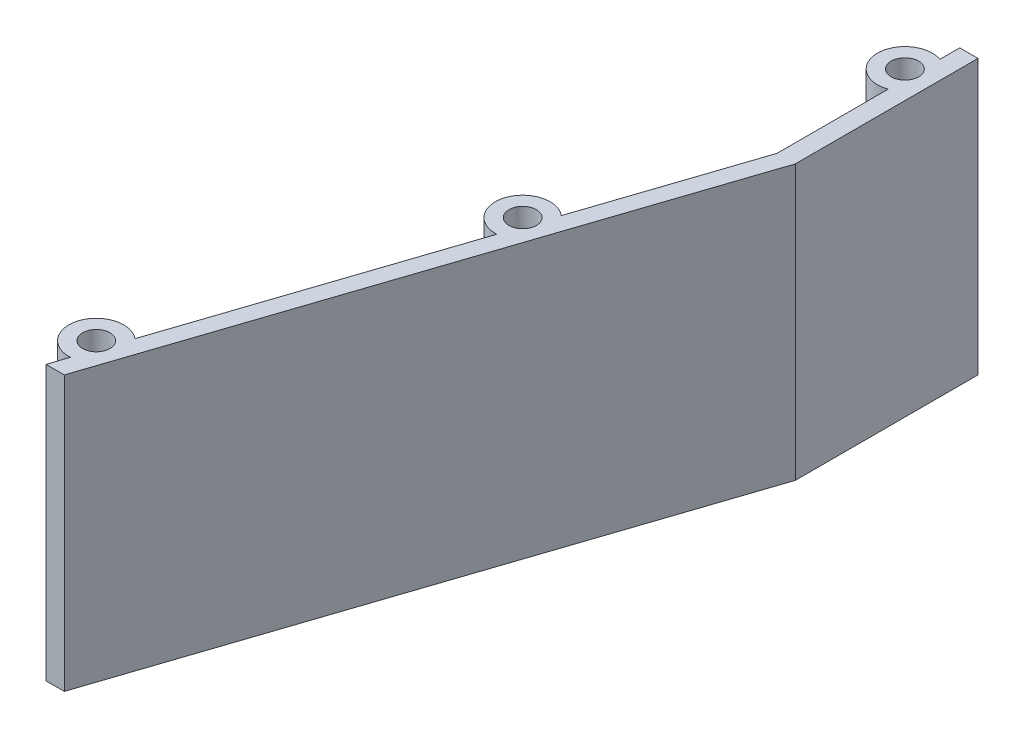
SolidWorks part; units mm, degrees
ref_plane "前视基准面" through (0, 0, 0) normal (0, 0, 1) x (1, 0, 0)
ref_plane "上视基准面" through (0, 0, 0) normal (0, 1, 0) x (1, 0, 0)
ref_plane "右视基准面" through (0, 0, 0) normal (1, 0, 0) x (0, 0, -1)
other "Configuration Table"
sketch "草图1" plane through (0, 0, 0) normal (0, 1, 0) x (1, 0, 0)
  line L0 (0, 0) -> (-5.9006, -17.7018)
  line L1 (-20, -60) -> (-18, -60)
  line L2 (-18, -60) -> (2, 0)
  line L3 (2, 0) -> (2, 20)
  line L4 (2, 20) -> (0, 20)
  line L5 (0, 20) -> (0, 17.8284)
  line L6 (-13.6514, -60) -> (49986.3486, -60) construction
  line L7 (2, 0) -> (0, 0) construction
  line L8 (0, 0) -> (0, -50000) construction
  line L9 (19.5808, -20) -> (-49980.4192, -20) construction
  line L10 (-7.6652, -22.9955) -> (-17.5673, -52.7018)
  line L11 (-14.7271, 15) -> (49985.2729, 15) construction
  line L12 (0, 12.1716) -> (0, 0)
  line L13 (-5.5059, -55) -> (-50005.5059, -55) construction
  line L14 (-19.3318, -57.9955) -> (-20, -60)
  circle A1 centre (-7.8289, -20) radius 1.5
  arc A2 (-5.9006, -17.7018) -> (-7.6652, -22.9955) centre (-7.8289, -20) ccw
  arc A3 (0, 17.8284) -> (0, 12.1716) centre (-1, 15) ccw
  circle A4 centre (-1, 15) radius 1.5
  arc A5 (-17.5673, -52.7018) -> (-19.3318, -57.9955) centre (-19.4956, -55) ccw
  circle A6 centre (-19.4956, -55) radius 1.5
  dimension "D6" = 5
  dimension "D7" = 3
  dimension "D9" = 6
  dimension "D10" = 3
  dimension "D11" = 6
  dimension "D12" = 3
  dimension "D1" = 2
  dimension "D2" = 80
  dimension "D3" = 60
  dimension "D4" = 20
  dimension "D5" = 40
  dimension "D8" = 5
extrude "凸台-拉伸1" add sketch "草图1" along normal blind 30
